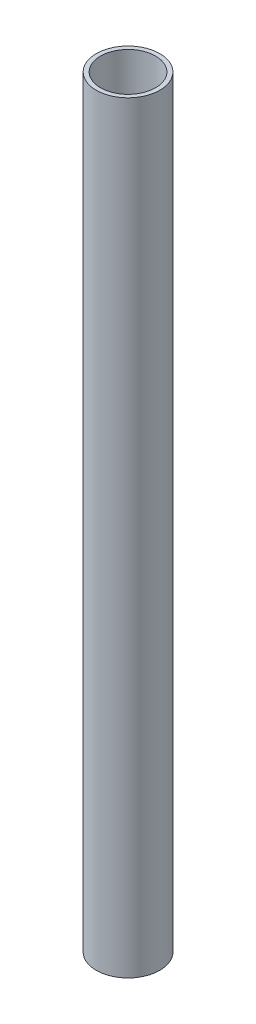
SolidWorks part; units mm, degrees
ref_plane "Front Plane" through (0, 0, 0) normal (0, 0, 1) x (1, 0, 0)
ref_plane "Top Plane" through (0, 0, 0) normal (0, 1, 0) x (1, 0, 0)
ref_plane "Right Plane" through (0, 0, 0) normal (1, 0, 0) x (0, 0, -1)
sketch "Sketch1" plane through (0, 0, 0) normal (0, 1, 0) x (1, 0, 0)
  circle A0 centre (0, 0) radius 6.5
  circle A1 centre (0, 0) radius 7.5
  dimension "D1" = 1
  dimension "D2" = 15
extrude "Boss-Extrude1" add sketch "Sketch1" along normal blind 180
